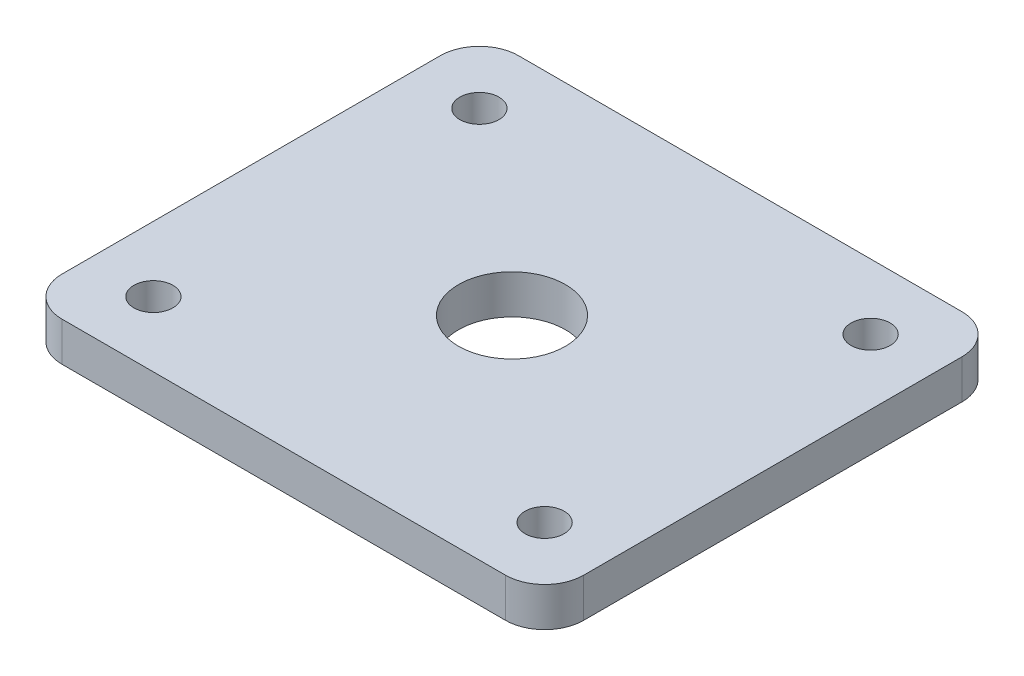
SolidWorks part; units mm, degrees
ref_plane "Front Plane" through (0, 0, 0) normal (0, 0, 1) x (1, 0, 0)
ref_plane "Top Plane" through (0, 0, 0) normal (0, 1, 0) x (1, 0, 0)
ref_plane "Right Plane" through (0, 0, 0) normal (1, 0, 0) x (0, 0, -1)
sketch "Sketch1" plane through (0, 0, 0) normal (0, 1, 0) x (1, 0, 0)
  line L0 (-5, 30) -> (-5, -5)
  line L5 (-5, -5) -> (35, -5)
  line L6 (35, 30) -> (35, -5)
  line L7 (-5, 30) -> (35, 30)
  circle A0 centre (0, 0) radius 1.5
  circle A1 centre (30, 0) radius 1.5
  circle A2 centre (30, 25) radius 1.5
  circle A3 centre (0, 25) radius 1.5
  circle A4 centre (15, 12.5) radius 12
  circle A5 centre (15, 12.5) radius 4.1
  dimension "D1" = 3
  dimension "D4" = 25
  dimension "D5" = 24
  dimension "D6" = 17.5
  dimension "D7" = 20
  dimension "D8" = 8.2
  dimension "D2" = 2
  dimension "D3" = 2
extrude "Boss-Extrude1" add sketch "Sketch1" along normal blind 3 contours L7 L0 L5 L6 A4 A3 A2 A1 A0 | A4 A5
fillet "Fillet1" radius 3 4 edges at (35, 1.5, 5) (-5, 1.5, 5) (35, 1.5, -30) (-5, 1.5, -30)
